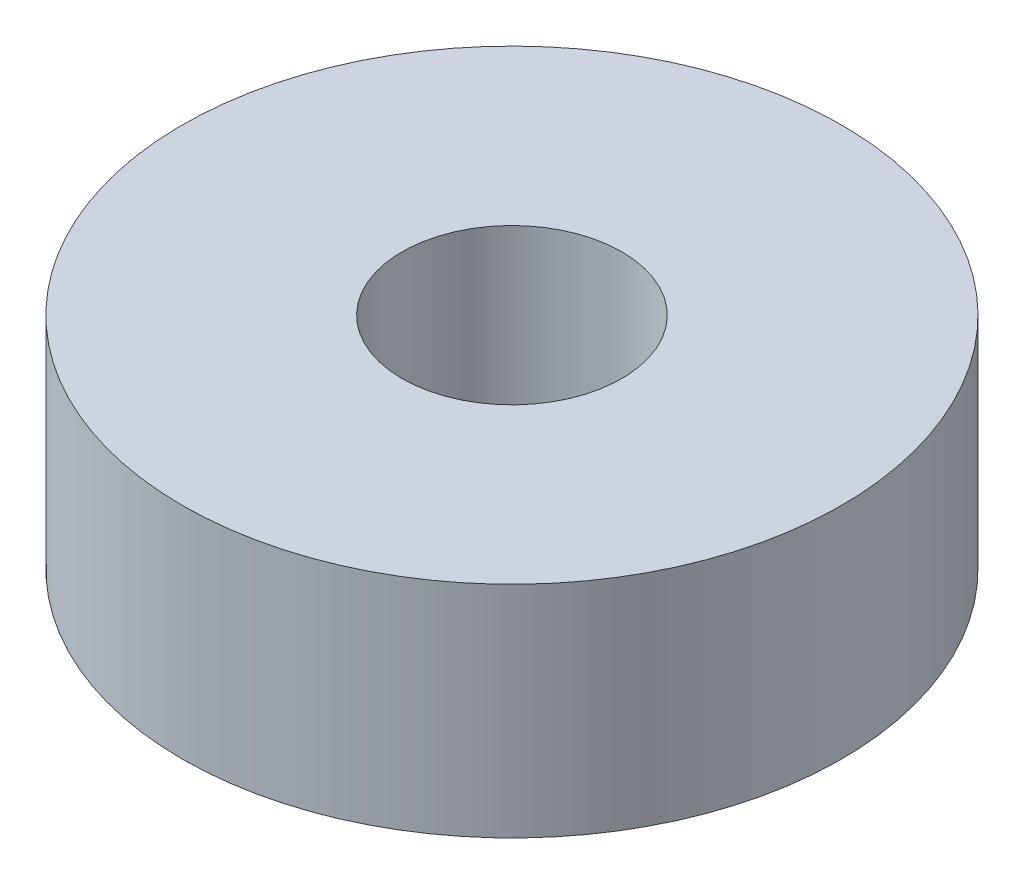
SolidWorks part; units mm, degrees
material "不锈钢 (铁素体)"
ref_plane "前视基准面" through (0, 0, 0) normal (0, 0, 1) x (1, 0, 0)
ref_plane "上视基准面" through (0, 0, 0) normal (0, 1, 0) x (1, 0, 0)
ref_plane "右视基准面" through (0, 0, 0) normal (1, 0, 0) x (0, 0, -1)
sketch "草图1" plane through (0, 0, 0) normal (0, 1, 0) x (1, 0, 0)
  circle A0 centre (0, 0) radius 2
  circle A1 centre (0, 0) radius 6
  dimension "D1" = 4
  dimension "D2" = 12
extrude "凸台-拉伸1" add sketch "草图1" along normal blind 4
